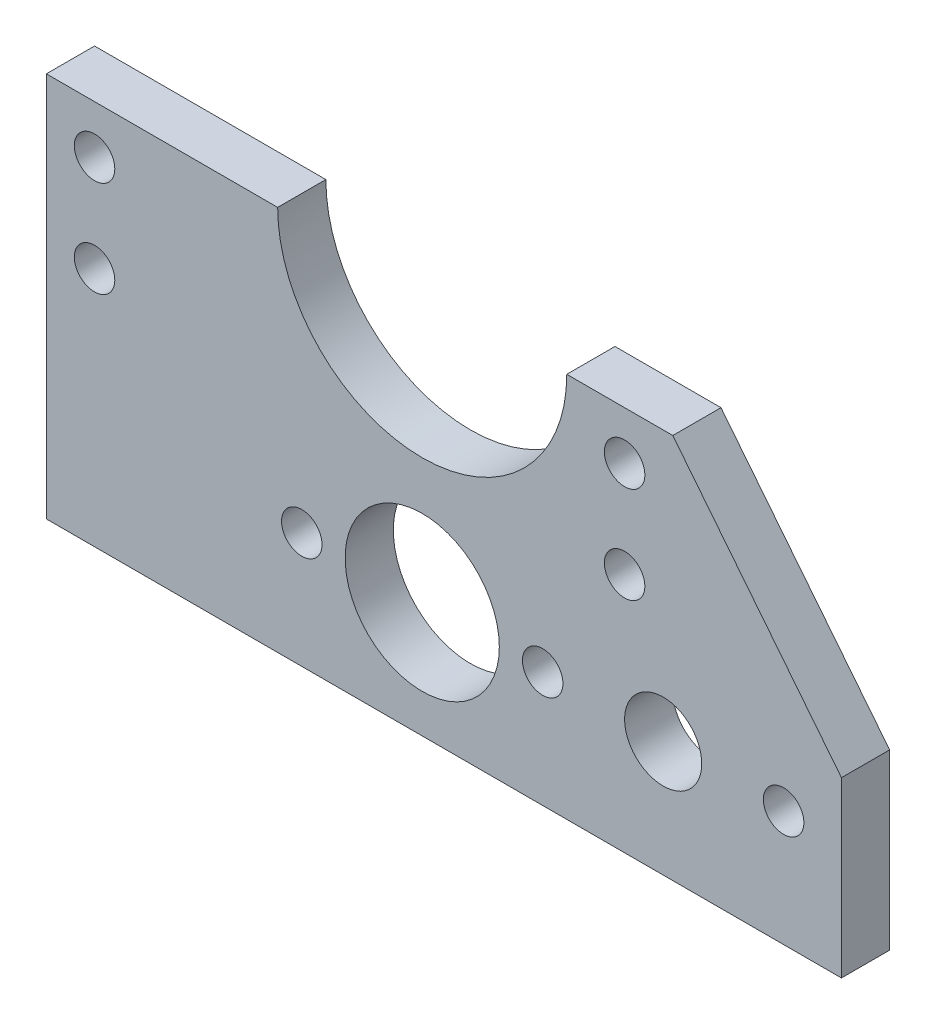
SolidWorks part; units mm, degrees
ref_plane "Front Plane" through (0, 0, 0) normal (0, 0, 1) x (1, 0, 0)
ref_plane "Top Plane" through (0, 0, 0) normal (0, 1, 0) x (1, 0, 0)
ref_plane "Right Plane" through (0, 0, 0) normal (1, 0, 0) x (0, 0, -1)
sketch "Sketch1" plane through (0, 0, 0) normal (0, 0, 1) x (1, 0, 0)
  line L3 (116.6115, 15.3385) -> (51.6115, 15.3385)
  line L4 (51.6115, 15.3385) -> (51.6115, -6.6615)
  line L8 (51.6115, -24.6615) -> (116.6115, -24.6615)
  line L9 (51.6115, -6.6615) -> (51.6115, -24.6615)
  line L10 (134.1115, -6.6615) -> (134.1115, -24.6615)
  line L11 (134.1115, -24.6615) -> (116.6115, -24.6615)
  line L12 (116.6115, 15.3385) -> (134.1115, -6.6615)
  circle A0 centre (56.6115, 10.3385) radius 2.1
  circle A1 centre (111.6115, 10.3385) radius 2.1
  circle A2 centre (56.6115, 0.3385) radius 2.1
  circle A3 centre (111.6115, 0.3385) radius 2.1
  circle A8 centre (115.6115, -12.6615) radius 4
  circle A9 centre (90.6115, -12.6615) radius 8
  circle A10 centre (78.1115, -12.6615) radius 2.1
  circle A11 centre (103.1115, -12.6615) radius 2.1
  circle A12 centre (128.1115, -12.6615) radius 2.1
  dimension "D7" = 4.2
  dimension "D8" = 4.2
  dimension "D9" = 4.2
  dimension "D10" = 4.2
  dimension "D11" = 5
  dimension "D12" = 5
  dimension "D13" = 17.5
  dimension "D14" = 5
  dimension "D15" = 1
  dimension "D16" = 10
  dimension "D17" = 10
  dimension "D18" = 5
  dimension "D19" = 8
  dimension "D20" = 16
  dimension "D21" = 25
  dimension "D23" = 4.2
  dimension "D24" = 12.5
  dimension "D25" = 4.2
  dimension "D26" = 12.5
  dimension "D27" = 4.2
  dimension "D28" = 12.5
  dimension "D2" = 65
  dimension "D4" = 40
  dimension "D5" = 22
extrude "Boss-Extrude1" add sketch "Sketch1" along normal blind 5
sketch "Sketch2" plane through (0, 0, 5) normal (0, 0, 1) x (1, 0, 0)
  line L0 (90.6115, -12.6615) -> (90.6115, 19.4472) construction
  line L1 (116.6115, 15.3385) -> (51.6115, 15.3385) construction
  circle A1 centre (90.6115, 15.3385) radius 15
  point P0 (90.6115, 15.3385)
extrude "Cut-Extrude1" cut sketch "Sketch2" against normal blind 10
move or copy body "Body-Move/Copy1" [suppressed] bodies to move or copy 101
